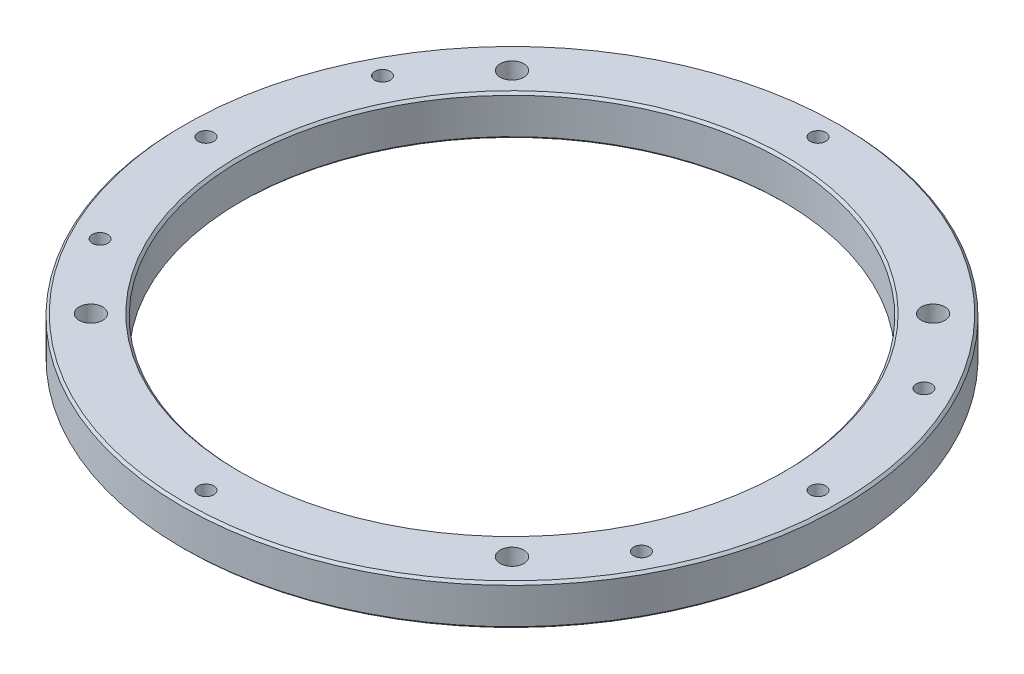
SolidWorks part; units mm, degrees
material "6061 合金"
ref_plane "正面" through (0, 0, 0) normal (0, 0, 1) x (1, 0, 0)
ref_plane "平面" through (0, 0, 0) normal (0, 1, 0) x (1, 0, 0)
ref_plane "右側面" through (0, 0, 0) normal (1, 0, 0) x (0, 0, -1)
sketch "ｽｹｯﾁ1" plane through (0, 0, 0) normal (0, 1, 0) x (1, 0, 0)
  circle A0 centre (0, 0) radius 57.5
  circle A1 centre (0, 0) radius 70
  dimension "D1" = 115
  dimension "D2" = 140
extrude "ﾎﾞｽ - 押し出し1" add sketch "ｽｹｯﾁ1" along normal blind 8.6
sketch "ｽｹｯﾁ2" plane through (0, 8.6, 0) normal (0, 1, 0) x (1, 0, 0)
  line L0 (0, 0) -> (-63.25, 0) construction
  line L1 (-44.7245, 44.7245) -> (0, 0) construction
  circle A0 centre (0, 0) radius 63.25 construction
  circle A1 centre (-44.7245, 44.7245) radius 2.5
  circle A2 centre (44.7245, 44.7245) radius 2.5
  circle A3 centre (44.7245, -44.7245) radius 2.5
  circle A4 centre (-44.7245, -44.7245) radius 2.5
  point P14 (0, 0)
  dimension "D1" = 126.5
  dimension "D2" = 5
  dimension "D4" = 45
  dimension "D3" = 4
extrude "ｶｯﾄ - 押し出し1" cut sketch "ｽｹｯﾁ2" against normal through all
chamfer "面取り1" distance 0.5 angle 45 4 edges at (0, 0, 70) (0, 8.6, 70) (0, 0, 57.5) (0, 8.6, 57.5)
sketch "ｽｹｯﾁ3" plane through (0, 8.6, 0) normal (0, 1, 0) x (1, 0, 0)
  line L0 (0, 0) -> (65, 0) construction
  line L1 (0, 0) -> (0, 58) construction
  circle A0 centre (0, 0) radius 65 construction
  circle A1 centre (65, 0) radius 1.65
  circle A2 centre (0, -65) radius 1.65
  circle A3 centre (-65, 0) radius 1.65
  circle A4 centre (0, 65) radius 1.65
  circle A5 centre (-57.5, 30) radius 1.65
  circle A6 centre (0, 0) radius 58 construction
  circle A7 centre (57.5, 30) radius 1.65
  circle A8 centre (57.5, -30) radius 1.65
  circle A9 centre (-57.5, -30) radius 1.65
  point P15 (0, 0)
  dimension "D1" = 130
  dimension "D3" = 3.3
  dimension "D2" = 3.3
  dimension "D4" = 115
  dimension "D5" = 60
extrude "ｶｯﾄ - 押し出し2" cut sketch "ｽｹｯﾁ3" against normal through all
